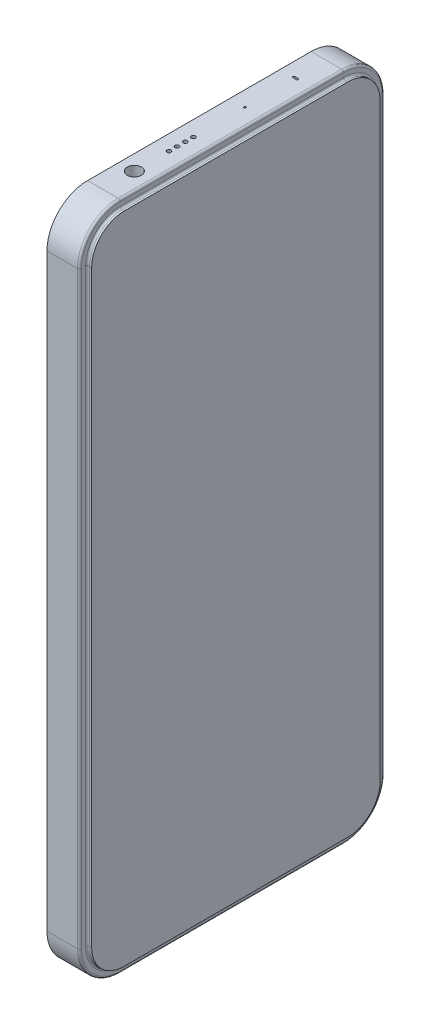
SolidWorks part; units mm, degrees
ref_plane "Front Plane" through (0, 0, 0) normal (0, 0, 1) x (1, 0, 0)
ref_plane "Top Plane" through (0, 0, 0) normal (0, 1, 0) x (1, 0, 0)
ref_plane "Right Plane" through (0, 0, 0) normal (1, 0, 0) x (0, 0, -1)
sketch "Sketch1" plane through (0, 0, 0) normal (1, 0, 0) x (0, 0, -1)
  line L1 (-37.5, 82.5) -> (37.5, 82.5)
  line L2 (-37.5, 82.5) -> (-37.5, -82.5)
  line L3 (-37.5, -82.5) -> (37.5, -82.5)
  line L4 (37.5, 82.5) -> (37.5, -82.5)
  line L5 (-37.5, 82.5) -> (37.5, -82.5) construction
  line L6 (-37.5, -82.5) -> (37.5, 82.5) construction
  point P0 (0, 0)
  dimension "D1" = 75
  dimension "D2" = 165
extrude "Boss-Extrude1" add sketch "Sketch1" along normal blind 7
sketch "Sketch2" plane through (0, 0, 0) normal (-1, 0, 0) x (0, 0, 1)
  line L4 (-37.5, 82.5) -> (-37.5, -82.5)
  line L5 (-37.5, -82.5) -> (37.5, -82.5)
  line L6 (37.5, -82.5) -> (37.5, 82.5)
  line L7 (37.5, 82.5) -> (-37.5, 82.5)
  line L8 (-37.5, 82.5) -> (-37.5, -82.5)
  line L9 (-37.5, -82.5) -> (37.5, -82.5)
  line L10 (37.5, -82.5) -> (37.5, 82.5)
  line L11 (37.5, 82.5) -> (-37.5, 82.5)
  dimension "D1" = 0
extrude "Boss-Extrude2" add sketch "Sketch2" along normal blind 1
sketch "Sketch3" plane through (-1, 0, 0) normal (-1, 0, 0) x (0, 0, 1)
  line L0 (37.5, 82.5) -> (-37.5, 82.5) construction
  line L1 (-27.5, 77.5) -> (-6.5, 77.5)
  line L2 (-32.5, 72.5) -> (-32.5, 39.5)
  line L3 (-27.5, 34.5) -> (-6.5, 34.5)
  line L4 (-1.5, 72.5) -> (-1.5, 39.5)
  line L5 (-37.5, 82.5) -> (-37.5, -82.5) construction
  arc A0 (-6.5, 77.5) -> (-1.5, 72.5) centre (-6.5, 72.5) cw
  arc A1 (-32.5, 39.5) -> (-27.5, 34.5) centre (-27.5, 39.5) ccw
  arc A2 (-6.5, 34.5) -> (-1.5, 39.5) centre (-6.5, 39.5) ccw
  arc A3 (-27.5, 77.5) -> (-32.5, 72.5) centre (-27.5, 72.5) ccw
  point P6 (-1.5, 77.5)
  point P11 (-1.5, 34.5)
  point P14 (-32.5, 77.5)
  dimension "D3" = 5
  dimension "D1" = 31
  dimension "D2" = 43
  dimension "D4" = 5
  dimension "D5" = 5
extrude "Boss-Extrude3" add sketch "Sketch3" along normal blind 1
sketch "Sketch4" plane through (-2, 0, 0) normal (-1, 0, 0) x (0, 0, 1)
  circle A0 centre (-24.088, 68.857) radius 7
  circle A1 centre (-24.088, 68.857) radius 6.25
  dimension "D1" = 14
  dimension "D2" = 12.5
extrude "Boss-Extrude4" add sketch "Sketch4" along normal blind 1
sketch "Sketch5" plane through (-2, 0, 0) normal (-1, 0, 0) x (0, 0, 1)
  circle A1 centre (-24.088, 68.857) radius 6.25
  circle A2 centre (-24.088, 68.857) radius 6.25
  dimension "D1" = 0
extrude "Boss-Extrude5" add sketch "Sketch5" along normal blind 0.99
sketch "Sketch6" plane through (-2, 0, 0) normal (-1, 0, 0) x (0, 0, 1)
  line L0 (-24.088, 68.857) -> (-24.088, 46.3557) construction
  circle A0 centre (-24.088, 46.3557) radius 6
  circle A1 centre (-24.088, 46.3557) radius 6.75
  dimension "D1" = 13.5
  dimension "D2" = 12
extrude "Boss-Extrude6" add sketch "Sketch6" along normal blind 1
sketch "Sketch7" plane through (-2, 0, 0) normal (-1, 0, 0) x (0, 0, 1)
  circle A1 centre (-24.088, 46.3557) radius 6
  circle A2 centre (-24.088, 46.3557) radius 6
  dimension "D1" = 0
extrude "Boss-Extrude7" add sketch "Sketch7" along normal blind 0.99
sketch "Sketch8" plane through (-2, 0, 0) normal (-1, 0, 0) x (0, 0, 1)
  line L0 (-6.5, 77.5) -> (-27.5, 77.5) construction
  line L1 (-1.5, 39.5) -> (-1.5, 72.5) construction
  circle A0 centre (-8.5, 56.5) radius 5.5658
  point P6 (-9.4578, 55.9922)
  dimension "D1" = 21
  dimension "D2" = 7
extrude "Boss-Extrude8" add sketch "Sketch8" against normal blind 5 separate body
sketch "Sketch9" plane through (-2, 0, 0) normal (-1, 0, 0) x (0, 0, 1)
  line L0 (-12.5, 43.5) -> (-6.5, 43.5) construction
  line L1 (-12.5, 44.75) -> (-6.5, 44.75)
  line L2 (-12.5, 42.25) -> (-6.5, 42.25)
  line L3 (-27.5, 34.5) -> (-6.5, 34.5) construction
  line L4 (-1.5, 39.5) -> (-1.5, 72.5) construction
  arc A0 (-12.5, 44.75) -> (-12.5, 42.25) centre (-12.5, 43.5) ccw
  arc A1 (-6.5, 42.25) -> (-6.5, 44.75) centre (-6.5, 43.5) ccw
  point P2 (-9.5, 43.5)
  dimension "D1" = 2.5
  dimension "D2" = 6
  dimension "D3" = 9
  dimension "D4" = 5
extrude "Boss-Extrude9" add sketch "Sketch9" against normal blind 5 separate body
fillet "Fillet1" radius 10 4 edges at (3, -82.5, -37.5) (3, -82.5, 37.5) (3, 82.5, 37.5) (3, 82.5, -37.5)
sketch "Sketch10" plane through (7, 0, 0) normal (1, 0, 0) x (0, 0, -1)
  line L0 (27.5, 80.5) -> (-27.5, 80.5)
  line L1 (-35.5, 72.5) -> (-35.5, -72.5)
  line L2 (-27.5, -80.5) -> (27.5, -80.5)
  line L3 (35.5, -72.5) -> (35.5, 72.5)
  arc A0 (-27.5, 80.5) -> (-35.5, 72.5) centre (-27.5, 72.5) ccw
  arc A1 (-35.5, -72.5) -> (-27.5, -80.5) centre (-27.5, -72.5) ccw
  arc A2 (27.5, -80.5) -> (35.5, -72.5) centre (27.5, -72.5) ccw
  arc A3 (35.5, 72.5) -> (27.5, 80.5) centre (27.5, 72.5) ccw
extrude "Boss-Extrude10" add sketch "Sketch10" along normal blind 1
fillet "Fillet2" radius 0.5 16 edges at (7, -79.5711, 34.5711) (7, 0, 37.5) (7, 79.5711, 34.5711) (7, 82.5, 0) (7, 79.5711, -34.5711) (7, 0, -37.5) (7, -79.5711, -34.5711) (7, -82.5, 0) (7, 80.5, 0) (7, 78.1569, 33.1569) (7, 0, 35.5) (7, -78.1569, 33.1569) (7, -80.5, 0) (7, -78.1569, -33.1569) (7, 0, -35.5) (7, 78.1569, -33.1569)
sketch "Sketch11" plane through (8, 0, 0) normal (1, 0, 0) x (0, 0, -1)
  circle A0 centre (0, 75.6233) radius 2
  point P4 (0, 0)
  dimension "D1" = 4
extrude "Boss-Extrude11" add sketch "Sketch11" against normal blind 0.9 separate body
sketch "Sketch13" plane through (-2, 0, 0) normal (-1, 0, 0) x (0, 0, 1)
  circle A0 centre (-8.5, 56.5) radius 1
  dimension "D1" = 2
extrude "Boss-Extrude12" add sketch "Sketch13" against normal blind 9 separate body contours A0
sketch "Sketch14" plane through (0, 82.5, 0) normal (0, 1, 0) x (1, 0, 0)
  line L3 (-1, -27.5) -> (6.5, -27.5) construction
  circle A0 centre (2.75, -19.747) radius 1.75
  point P2 (0, 0)
  point P6 (2.75, -27.5)
  point P19 (0, 0)
  dimension "D1" = 3.5
sketch "Sketch16" plane through (0, 82.5, 0) normal (0, 1, 0) x (1, 0, 0)
  point P0 (2.75, -66.994)
  point P3 (2.75, -19.747)
extrude "Cut-Extrude2" cut sketch "Sketch14" against normal blind 15 contours A0
sketch "Sketch17" plane through (0, 82.5, 0) normal (0, 1, 0) x (1, 0, 0)
  circle A0 centre (2.75, -11.2295) radius 0.5
  dimension "D1" = 1
extrude "Cut-Extrude3" cut sketch "Sketch17" against normal blind 2 contours A0
pattern_linear "LPattern1" count 4 spacing 2 along (0, 0, -1) of "Cut-Extrude3"
sketch "Sketch18" plane through (0, 82.5, 0) normal (0, 1, 0) x (1, 0, 0)
  circle A0 centre (2.75, 7.4579) radius 0.25
  dimension "D1" = 0.5
extrude "Cut-Extrude4" cut sketch "Sketch18" against normal blind 5
sketch "Sketch19" plane through (0, 82.5, 0) normal (0, 1, 0) x (1, 0, 0)
  line L0 (2.35, 19.9403) -> (3.15, 19.9403) construction
  line L1 (2.35, 20.1903) -> (3.15, 20.1903)
  line L2 (2.35, 19.6903) -> (3.15, 19.6903)
  line L3 (6.5, 27.5) -> (-1, 27.5) construction
  arc A0 (2.35, 20.1903) -> (2.35, 19.6903) centre (2.35, 19.9403) ccw
  arc A1 (3.15, 19.6903) -> (3.15, 20.1903) centre (3.15, 19.9403) ccw
  point P2 (2.75, 19.9403)
  point P9 (2.75, 27.5)
  dimension "D1" = 0.5
  dimension "D2" = 0.8
extrude "Cut-Extrude5" cut sketch "Sketch19" against normal blind 2
sketch "Sketch20" plane through (0, -82.5, 0) normal (0, -1, 0) x (1, 0, 0)
  circle A0 centre (2.75, -23.8305) radius 0.5
  dimension "D1" = 1
extrude "Cut-Extrude6" cut sketch "Sketch20" against normal blind 2
pattern_linear "LPattern2" count 5 spacing 2 along (0, 0, 1) of "Cut-Extrude6"
sketch "Sketch21" plane through (0, -82.5, 0) normal (0, -1, 0) x (1, 0, 0)
  line L0 (2.75, 3) -> (2.75, -3) construction
  line L1 (4.5, 3) -> (4.5, -3)
  line L2 (1, 3) -> (1, -3)
  line L3 (-1, -27.5) -> (6.5, -27.5) construction
  arc A0 (4.5, 3) -> (1, 3) centre (2.75, 3) ccw
  arc A1 (1, -3) -> (4.5, -3) centre (2.75, -3) ccw
  point P2 (2.75, 0)
  point P7 (0, 0)
  point P11 (2.75, -27.5)
  dimension "D1" = 3.5
  dimension "D2" = 6
extrude "Cut-Extrude7" cut sketch "Sketch21" against normal blind 5
sketch "Sketch22" plane through (0, -77.5, 0) normal (0, -1, 0) x (1, 0, 0)
  line L5 (2.71, 2.7173) -> (2.79, 2.7173)
  line L6 (2.7, 2.7073) -> (2.7, -3.2727)
  line L7 (2.71, -3.2827) -> (2.79, -3.2827)
  line L8 (2.8, 2.7073) -> (2.8, -3.2727)
  arc A0 (4.5, 3) -> (1, 3) centre (2.75, 3) ccw construction
  arc A1 (2.79, 2.7173) -> (2.8, 2.7073) centre (2.79, 2.7073) cw
  arc A2 (2.7, -3.2727) -> (2.71, -3.2827) centre (2.71, -3.2727) ccw
  arc A3 (2.79, -3.2827) -> (2.8, -3.2727) centre (2.79, -3.2727) ccw
  arc A4 (2.71, 2.7173) -> (2.7, 2.7073) centre (2.71, 2.7073) ccw
  point P9 (2.75, 4.75)
  point P10 (2.75, 2.7173)
  point P13 (2.8, 2.7173)
  point P18 (2.8, -3.2827)
  point P21 (2.7, 2.7173)
  dimension "D3" = 0.01
  dimension "D4" = 0.01
  dimension "D5" = 0.01
  dimension "D6" = 0.01
  dimension "D1" = 0.1
  dimension "D2" = 6
extrude "Boss-Extrude13" add sketch "Sketch22" along normal blind 2.5
sketch "Sketch23" plane through (0, -77.5, 0) normal (0, -1, 0) x (1, 0, 0)
  line L0 (2.75, 3) -> (2.75, -3) construction
  line L1 (4.4, 3) -> (4.4, -3)
  line L2 (1.1, 3) -> (1.1, -3)
  arc A0 (4.4, 3) -> (1.1, 3) centre (2.75, 3) ccw
  arc A1 (1.1, -3) -> (4.4, -3) centre (2.75, -3) ccw
  point P4 (2.75, 0)
  dimension "D1" = 3.3
  dimension "D2" = 6
extrude "Boss-Extrude14" add sketch "Sketch23" along normal blind 1.5
sketch "Sketch24" plane through (0, -82.5, 0) normal (0, -1, 0) x (1, 0, 0)
  circle A0 centre (2.8, 10.5971) radius 0.25
  dimension "D1" = 0.5
extrude "Cut-Extrude8" cut sketch "Sketch24" against normal blind 3
sketch "Sketch25" plane through (0, -82.5, 0) normal (0, -1, 0) x (1, 0, 0)
  line L0 (2.8, 14.2746) -> (2.8, 22.2746) construction
  line L1 (2.05, 14.2746) -> (2.05, 22.2746)
  line L2 (3.55, 14.2746) -> (3.55, 22.2746)
  arc A0 (2.05, 14.2746) -> (3.55, 14.2746) centre (2.8, 14.2746) ccw
  arc A1 (3.55, 22.2746) -> (2.05, 22.2746) centre (2.8, 22.2746) ccw
  point P3 (2.8, 18.2746)
  dimension "D1" = 1.5
  dimension "D2" = 8
extrude "Cut-Extrude9" cut sketch "Sketch25" against normal blind 0.09 contours L1 A1 L2 A0
sketch "Sketch26" plane through (0, -82.41, 0) normal (0, -1, 0) x (1, 0, 0)
  circle A0 centre (2.8, 22.2746) radius 0.1586
extrude "Cut-Extrude10" cut sketch "Sketch26" against normal blind 0.5
